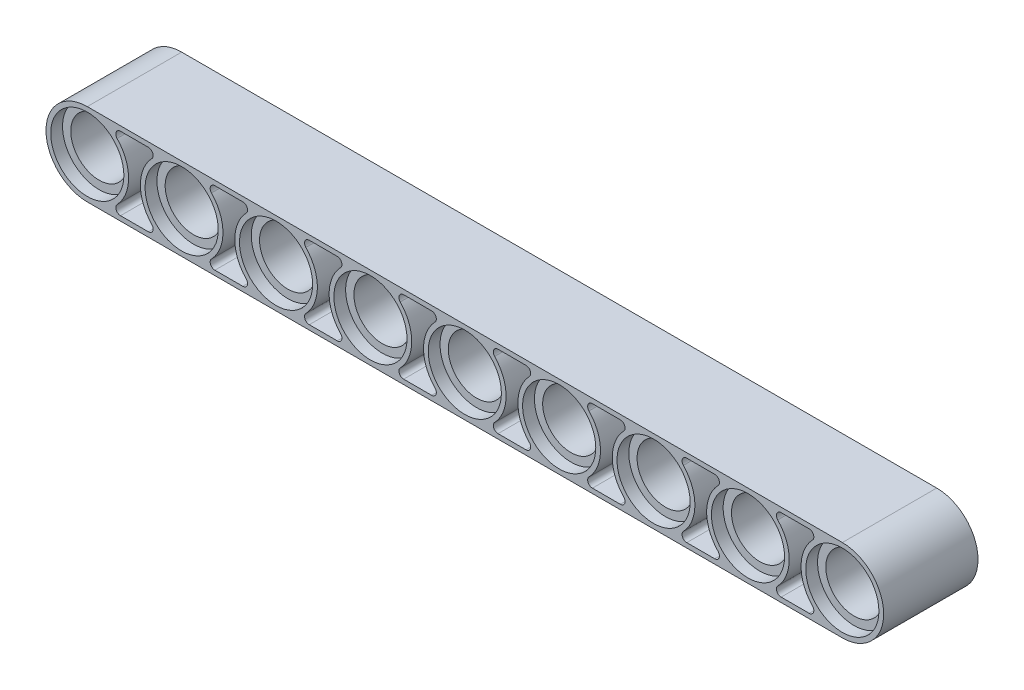
SolidWorks part; units mm, degrees
ref_plane "Front Plane" through (0, 0, 0) normal (0, 0, 1) x (1, 0, 0)
ref_plane "Top Plane" through (0, 0, 0) normal (0, 1, 0) x (1, 0, 0)
ref_plane "Right Plane" through (0, 0, 0) normal (1, 0, 0) x (0, 0, -1)
sketch "Sketch1" plane through (0, 0, 0) normal (0, 0, 1) x (1, 0, 0)
  line L0 (0, 0) -> (-64, 0) construction
  line L1 (0, -3.5) -> (-64, -3.5)
  line L2 (0, 3.5) -> (-64, 3.5)
  arc A0 (0, -3.5) -> (0, 3.5) centre (0, 0) ccw
  arc A1 (-64, 3.5) -> (-64, -3.5) centre (-64, 0) ccw
  point P3 (-32, 0)
  point P8 (-67.5, 0)
  point P9 (3.5, 0)
  dimension "D1" = 71
  dimension "D2" = 7
extrude "Boss-Extrude2" add sketch "Sketch1" along normal blind 8
sketch "Sketch5" plane through (0, 0, 0) normal (0, 0, -1) x (-1, 0, 0)
  circle A0 centre (0, 0) radius 3.1
extrude "Cut-Extrude4" cut sketch "Sketch5" against normal blind 1
sketch "Sketch6" plane through (0, 0, 8) normal (0, 0, 1) x (1, 0, 0)
  circle A0 centre (0, 0) radius 3.1
extrude "Cut-Extrude5" cut sketch "Sketch6" against normal blind 1
sketch "Sketch7" plane through (0, 0, 7) normal (0, 0, 1) x (1, 0, 0)
  circle A0 centre (0, 0) radius 2.4
extrude "Cut-Extrude6" cut sketch "Sketch7" against normal through all both and the other way through all
pattern_linear "LPattern1" count 9 spacing 8 along (-1, 0, 0) of "Cut-Extrude6", "Cut-Extrude5", "Cut-Extrude4"
sketch "Sketch8" plane through (0, 0, 0) normal (0, 0, -1) x (-1, 0, 0)
  line L0 (2.8142, 3.1) -> (5.1858, 3.1)
  line L1 (2.8142, -3.1) -> (5.1858, -3.1)
  arc A0 (2.5256, -2.4231) -> (2.5256, 2.4231) centre (0, 0) ccw
  arc A1 (5.4744, 2.4231) -> (5.4744, -2.4231) centre (8, 0) ccw
  arc A6 (2.5256, -2.4231) -> (2.8142, -3.1) centre (2.8142, -2.7) ccw
  arc A7 (5.1858, -3.1) -> (5.4744, -2.4231) centre (5.1858, -2.7) ccw
  arc A8 (5.4744, 2.4231) -> (5.1858, 3.1) centre (5.1858, 2.7) ccw
  arc A9 (2.8142, 3.1) -> (2.5256, 2.4231) centre (2.8142, 2.7) ccw
  dimension "D1" = 7
  dimension "D2" = 7
  dimension "D3" = 0.4
extrude "Cut-Extrude7" cut sketch "Sketch8" against normal through all
pattern_linear "LPattern2" count 8 spacing 8 along (-1, 0, 0) of "Cut-Extrude7"
